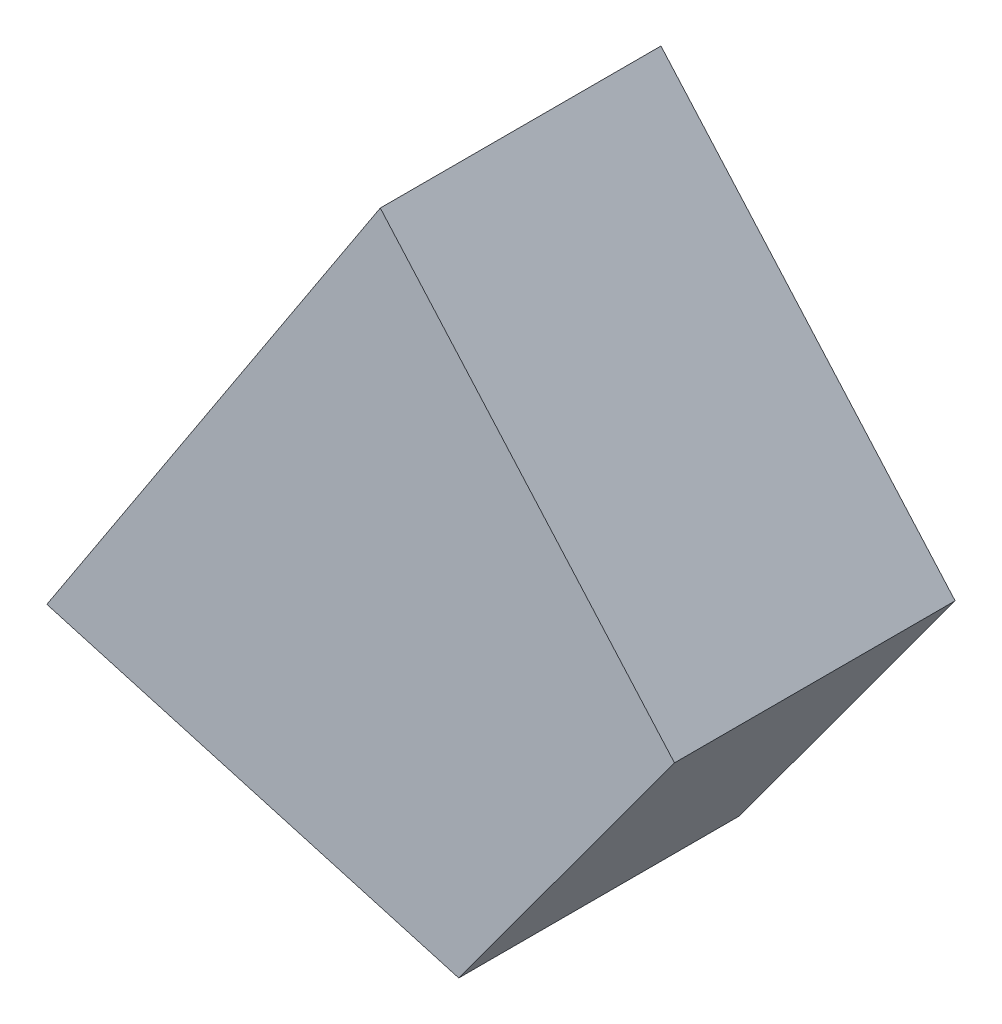
SolidWorks part; units mm, degrees
ref_plane "Front Plane" through (0, 0, 0) normal (0, 0, 1) x (1, 0, 0)
ref_plane "Top Plane" through (0, 0, 0) normal (0, 1, 0) x (1, 0, 0)
ref_plane "Right Plane" through (0, 0, 0) normal (1, 0, 0) x (0, 0, -1)
sketch "Sketch1" plane through (0, 0, 0) normal (0, 0, 1) x (1, 0, 0)
  line L0 (-13, -3) -> (8, -9)
  line L1 (8, -9) -> (19, 6)
  line L2 (19, 6) -> (4, 23)
  line L3 (4, 23) -> (-13, -3)
extrude "Boss-Extrude1" add sketch "Sketch1" along normal blind 14.31
